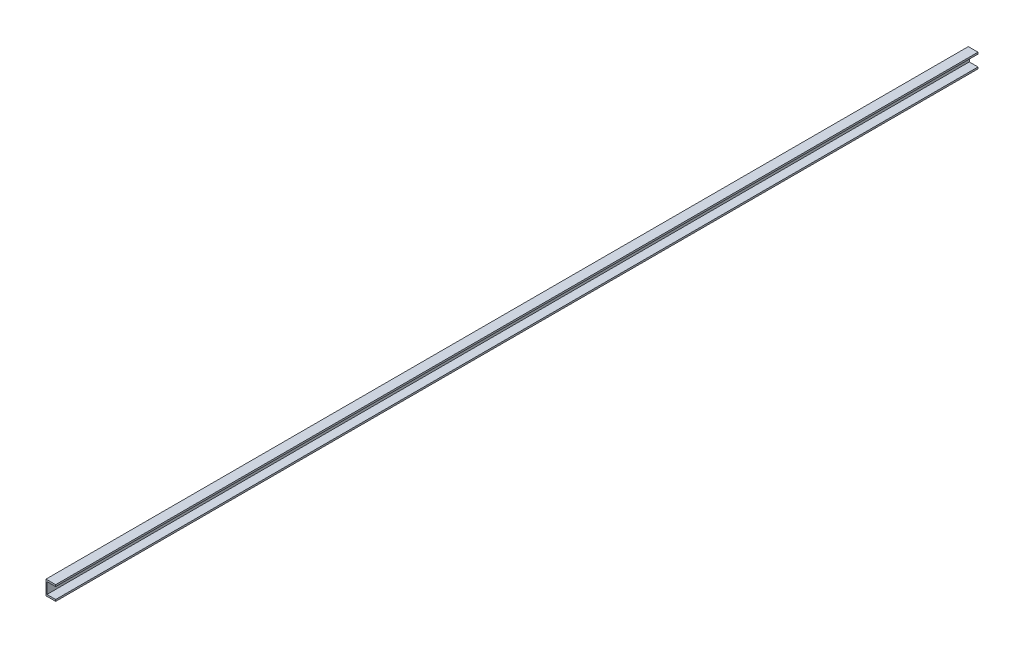
SolidWorks part; units mm, degrees
material "ASTM A992 Steel"
ref_plane "Front" through (0, 0, 0) normal (0, 0, 1) x (1, 0, 0)
ref_plane "Top" through (0, 0, 0) normal (0, 1, 0) x (1, 0, 0)
ref_plane "Right" through (0, 0, 0) normal (1, 0, 0) x (0, 0, -1)
sketch "Sketch1" plane through (0, 0, 0) normal (0, 0, 1) x (1, 0, 0)
  line L0 (0, 0) -> (0, 41.1578)
  line L1 (0, 41.1578) -> (53.086, 41.1578)
  line L2 (53.086, 41.1578) -> (53.086, 31.8614)
  line L3 (53.086, 31.8614) -> (5.334, 31.8614)
  line L4 (5.334, 31.8614) -> (5.334, -29.2823)
  line L5 (5.334, -29.2823) -> (53.086, -29.2823)
  line L6 (53.086, -29.2823) -> (53.086, -38.5787)
  line L7 (53.086, -38.5787) -> (0, -38.5787)
  line L8 (0, -38.5787) -> (0, 0)
  dimension "D1" = 53.086
  dimension "D2" = 53.086
  dimension "D3" = 9.2964
  dimension "D4" = 9.2964
  dimension "D5" = 5.334
extrude "Boss-Extrude1" add sketch "Sketch1" along normal blind 5062
